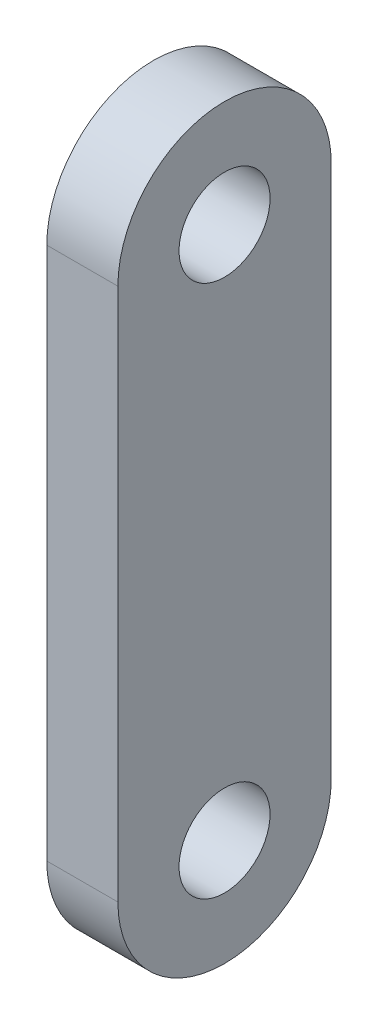
SolidWorks part; units mm, degrees
ref_plane "Front Plane" through (0, 0, 0) normal (0, 0, 1) x (1, 0, 0)
ref_plane "Top Plane" through (0, 0, 0) normal (0, 1, 0) x (1, 0, 0)
ref_plane "Right Plane" through (0, 0, 0) normal (1, 0, 0) x (0, 0, -1)
sketch "Sketch1" plane through (0, 0, 0) normal (1, 0, 0) x (0, 0, -1)
  line L0 (0, 0) -> (0, 23.8125) construction
  line L1 (-4.7625, 0) -> (-4.7625, 23.8125)
  line L2 (4.7625, 0) -> (4.7625, 23.8125)
  arc A0 (-4.7625, 0) -> (4.7625, 0) centre (0, 0) ccw
  arc A1 (4.7625, 23.8125) -> (-4.7625, 23.8125) centre (0, 23.8125) ccw
  circle A2 centre (0, 23.8125) radius 2.032
  circle A3 centre (0, 0) radius 2.032
  point P3 (0, 11.9062)
  dimension "D2" = 9.525
  dimension "D3" = 4.064
  dimension "D1" = 23.8125
extrude "Boss-Extrude1" add sketch "Sketch1" along normal blind 3.175
